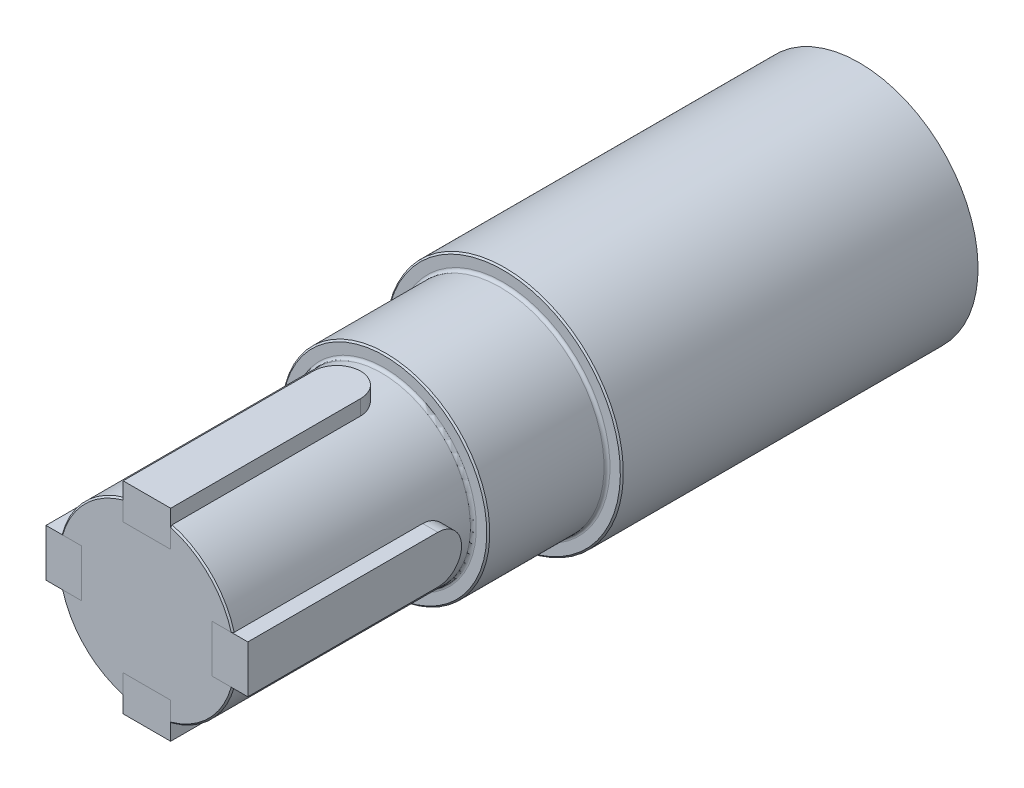
SolidWorks part; units mm, degrees
ref_plane "Front Plane" through (0, 0, 0) normal (0, 0, 1) x (1, 0, 0)
ref_plane "Top Plane" through (0, 0, 0) normal (0, 1, 0) x (1, 0, 0)
ref_plane "Right Plane" through (0, 0, 0) normal (1, 0, 0) x (0, 0, -1)
sketch "Sketch1" plane through (0, 0, 0) normal (1, 0, 0) x (0, 0, -1)
  line L0 (0, 0) -> (0, 15)
  line L1 (0, 15) -> (40, 15)
  line L2 (40, 15) -> (40, 17.5)
  line L3 (40, 17.5) -> (60, 17.5)
  line L4 (60, 17.5) -> (60, 20)
  line L5 (60, 20) -> (120, 20)
  line L6 (120, 20) -> (120, 0)
  line L7 (120, 0) -> (0, 0)
  dimension "D1" = 15
  dimension "D2" = 2.5
  dimension "D3" = 2.5
  dimension "D4" = 40
  dimension "D5" = 20
  dimension "D6" = 60
revolve "Revolve1" add sketch "Sketch1" angle 360 about L7
sketch "Sketch2" plane through (0, 0, 0) normal (0, 1, 0) x (1, 0, 0)
  line L0 (0, 0) -> (0, 32) construction
  line L1 (-4, 0) -> (-4, 32)
  line L2 (4, 0) -> (4, 32)
  arc A0 (-4, 0) -> (4, 0) centre (0, 0) ccw
  arc A1 (4, 32) -> (-4, 32) centre (0, 32) ccw
  point P3 (0, 16)
  point P8 (0, 0)
  point P9 (0, 0)
  dimension "D1" = 8
  dimension "D2" = 32
extrude "Cut-Extrude1" cut sketch "Sketch2" along normal blind 10 from offset 11
pattern_circular "CirPattern1" count 4 over 360 about axis through (0, 0, 0) along (0, 0, 1) of "Cut-Extrude1"
sketch "Sketch3" plane through (0, 11, 0) normal (0, 1, 0) x (1, 0, 0)
  line L3 (4, 0) -> (4, 32)
  line L4 (-4, 32) -> (-4, 0)
  line L5 (-4, 0) -> (4, 0)
  line L6 (4, 0) -> (4, 32)
  line L7 (-4, 32) -> (-4, 0)
  line L9 (-4, 0) -> (4, 0)
  arc A1 (4, 32) -> (-4, 32) centre (0, 32) ccw
  arc A2 (4, 32) -> (-4, 32) centre (0, 32) ccw
  dimension "D1" = 0
extrude "Boss-Extrude1" add sketch "Sketch3" along normal blind 6 separate body
pattern_circular "CirPattern2" count 4 over 360 about axis through (0, 0, 0) along (0, 0, 1) of bodies 106
fillet "Fillet1" radius 0.5 2 edges at (0, 17.5, -60) (0, 15, -40)
chamfer "Chamfer1" distance 0.25 angle 45 6 edges at (-10.6066, 10.6066, 0) (-10.6066, -10.6066, 0) (10.6066, -10.6066, 0) (10.6066, 10.6066, 0) (0, 20, -60) (0, 17.5, -40)
